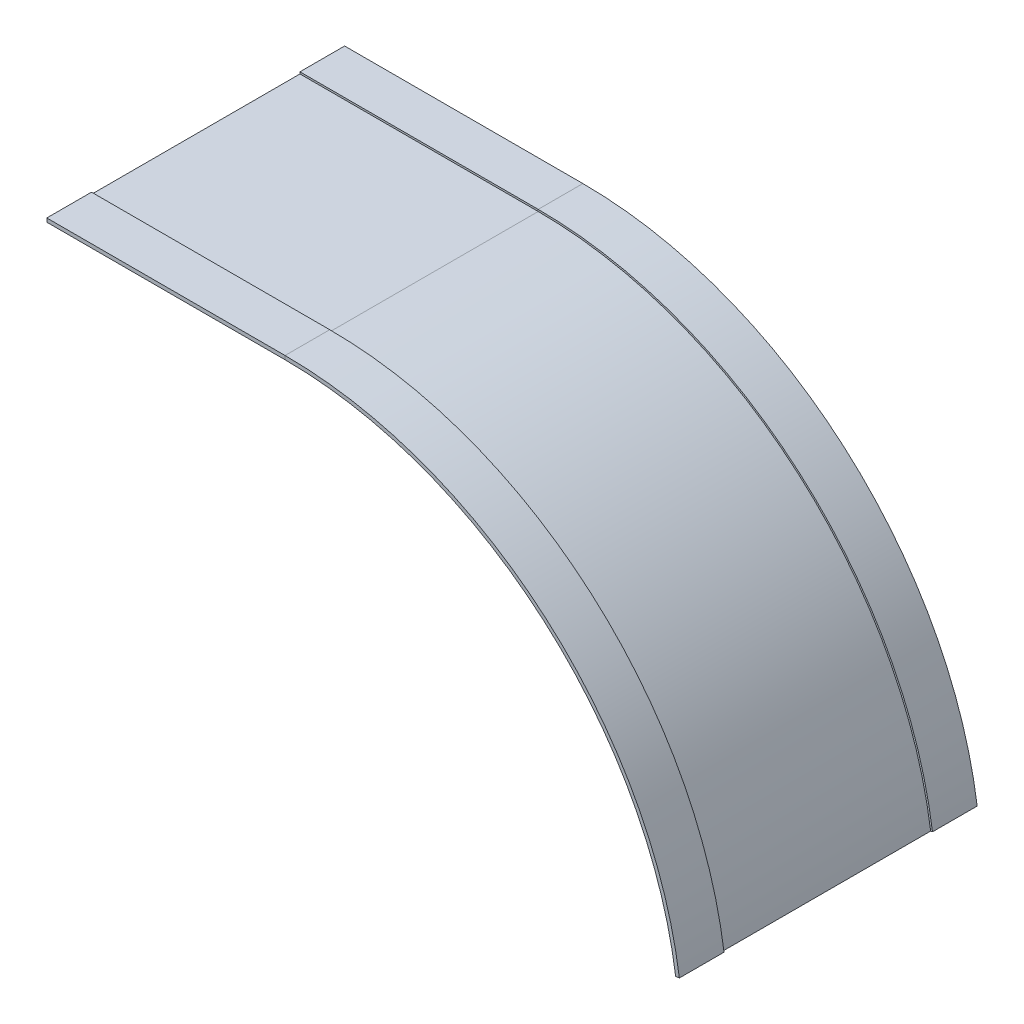
SolidWorks part; units mm, degrees
material "SHEET STEEL"
ref_plane "Front Plane" through (0, 0, 0) normal (0, 0, 1) x (1, 0, 0)
ref_plane "Top Plane" through (0, 0, 0) normal (0, 1, 0) x (1, 0, 0)
ref_plane "Right Plane" through (0, 0, 0) normal (1, 0, 0) x (0, 0, -1)
sketch "Sketch1" plane through (0, 0, 0) normal (0, 0, 1) x (1, 0, 0)
  line L0 (-190.8848, 85.8982) -> (-89.2848, 85.8982)
  arc A0 (-89.2848, 85.8982) -> (77.2968, -58.5643) centre (-89.2848, -82.3768) cw
  dimension "D2" = 168.275
  dimension "D1" = 101.6
  dimension "D3" = 23.8125
ref_plane "Plane1" through (-190.8848, 0, 0) normal (1, 0, 0) x (0, 0, -1)
sketch "Sketch2" plane through (-190.8848, 0, 0) normal (1, 0, 0) x (0, 0, -1)
  line L0 (0, 85.8982) -> (50000, 85.8982) construction
  line L1 (0, 85.8982) -> (0, 50085.8982) construction
  line L2 (-63.5, 85.8982) -> (63.5, 85.8982)
  line L3 (63.5, 85.8982) -> (63.5, 87.4857)
  line L4 (63.5, 87.4857) -> (44.45, 87.4857)
  line L5 (44.45, 87.4857) -> (44.45, 86.6919)
  line L6 (44.45, 86.6919) -> (-44.45, 86.6919)
  line L7 (-44.45, 86.6919) -> (-44.45, 87.4857)
  line L8 (-44.45, 87.4857) -> (-63.5, 87.4857)
  line L9 (-63.5, 87.4857) -> (-63.5, 85.8982)
  dimension "D1" = 127
  dimension "D2" = 1.5875
  dimension "D3" = 0.7937
  dimension "D4" = 19.05
sweep "Sweep2" add profiles "Sketch2" path "Sketch1"
